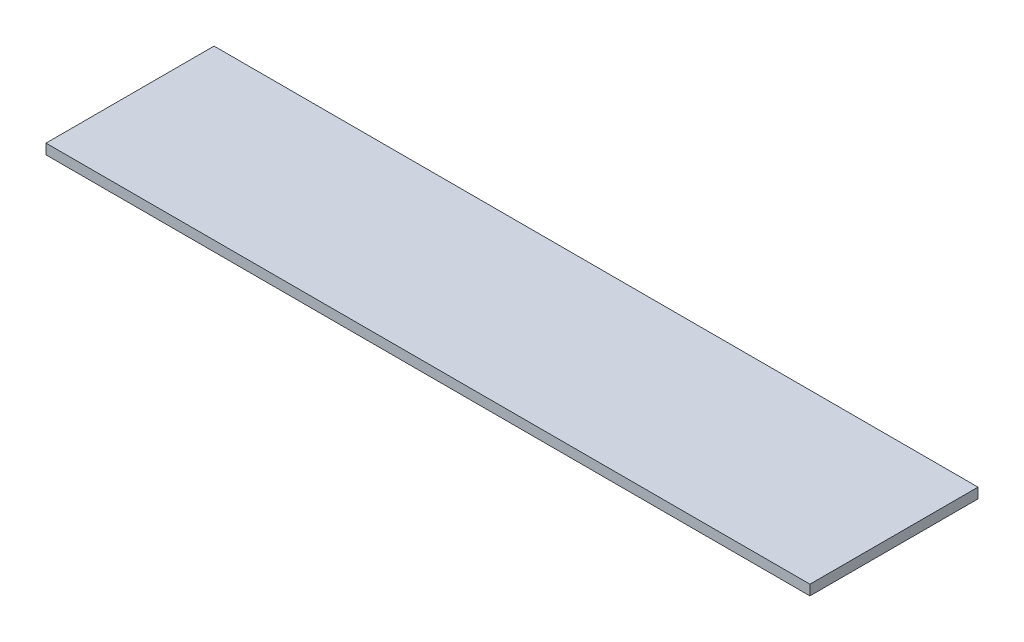
SolidWorks part; units mm, degrees
ref_plane "Front Plane" through (0, 0, 0) normal (0, 0, 1) x (1, 0, 0)
ref_plane "Top Plane" through (0, 0, 0) normal (0, 1, 0) x (1, 0, 0)
ref_plane "Right Plane" through (0, 0, 0) normal (1, 0, 0) x (0, 0, -1)
sketch "Sketch1" plane through (0, 0, 0) normal (0, 1, 0) x (1, 0, 0)
  line L1 (-75, -16.5) -> (75, -16.5)
  line L2 (-75, -16.5) -> (-75, 16.5)
  line L3 (-75, 16.5) -> (75, 16.5)
  line L4 (75, -16.5) -> (75, 16.5)
  line L5 (-75, -16.5) -> (75, 16.5) construction
  line L6 (-75, 16.5) -> (75, -16.5) construction
  point P0 (0, 0)
  dimension "D1" = 150
  dimension "D2" = 33
extrude "Boss-Extrude1" add sketch "Sketch1" along normal mid plane 2
